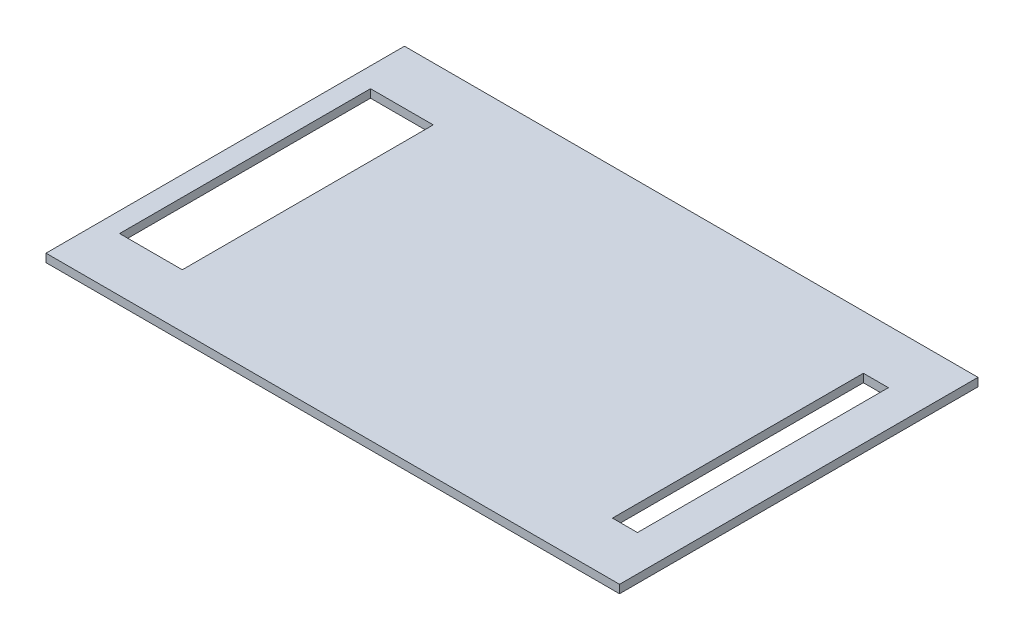
SolidWorks part; units mm, degrees
material "Beech"
ref_plane "Front Plane" through (0, 0, 0) normal (0, 0, 1) x (1, 0, 0)
ref_plane "Top Plane" through (0, 0, 0) normal (0, 1, 0) x (1, 0, 0)
ref_plane "Right Plane" through (0, 0, 0) normal (1, 0, 0) x (0, 0, -1)
sketch "Sketch1" plane through (0, 0, 0) normal (0, 1, 0) x (1, 0, 0)
  line L0 (-406.4, 127) -> (0, 127) construction
  line L1 (-406.4, 254) -> (0, 254)
  line L2 (-406.4, 254) -> (-406.4, 0)
  line L3 (-406.4, 0) -> (0, 0)
  line L4 (0, 254) -> (0, 0)
  line L5 (-392.3665, 254) -> (-392.3665, 0) construction
  line L6 (-25.4, 254) -> (-25.4, 0) construction
  line L7 (-25.4, 38.1) -> (-43.1165, 38.1)
  line L8 (-392.3665, 127) -> (-347.9165, 127)
  line L9 (-392.3665, 38.1) -> (-392.3665, 215.9)
  line L10 (-392.3665, 215.9) -> (-347.9165, 215.9)
  line L11 (-347.9165, 38.1) -> (-347.9165, 215.9)
  line L12 (-25.4, 127) -> (-43.1165, 127)
  line L13 (-25.4, 38.1) -> (-25.4, 215.9)
  line L14 (-25.4, 215.9) -> (-43.1165, 215.9)
  line L15 (-43.1165, 38.1) -> (-43.1165, 215.9)
  line L16 (-392.3665, 38.1) -> (-347.9165, 38.1)
  dimension "D1" = 406.4
  dimension "D2" = 254
  dimension "D3" = 304.8
  dimension "D4" = 25.4
  dimension "D5" = 44.45
  dimension "D6" = 88.9
  dimension "D7" = 88.9
  dimension "D8" = 17.7165
extrude "Boss-Extrude1" add sketch "Sketch1" along normal blind 5.842 contours L4 L1 L2 L3 L16 L9 L10 L11 L7 L15 L14 L13
